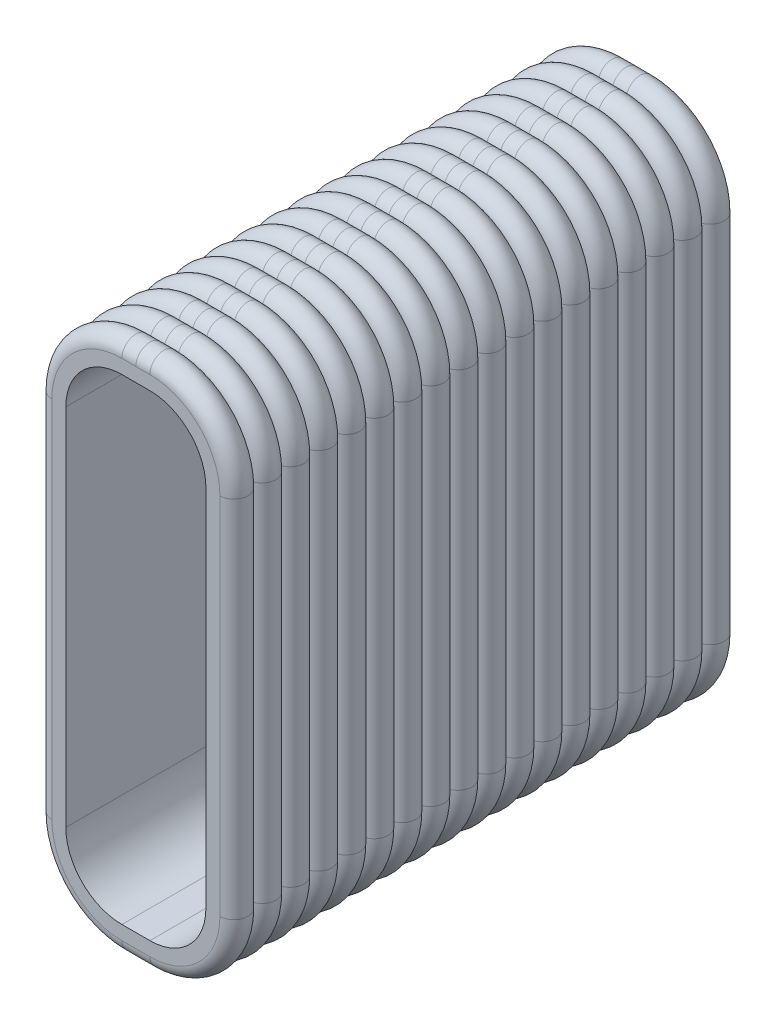
SolidWorks part; units mm, degrees
material "Copper-Cobalt-Beryllium alloy, UNS C17500"
ref_plane "Front Plane" through (0, 0, 0) normal (0, 0, 1) x (1, 0, 0)
ref_plane "Top Plane" through (0, 0, 0) normal (0, 1, 0) x (1, 0, 0)
ref_plane "Right Plane" through (0, 0, 0) normal (1, 0, 0) x (0, 0, -1)
sketch "Sketch1" plane through (0, 0, 0) normal (0, 0, 1) x (1, 0, 0)
  line L0 (-1.75, 3.25) -> (-1.75, -3.25)
  line L1 (-0.25, 4.25) -> (0.25, 4.25)
  line L2 (-1.25, 3.25) -> (-1.25, -3.25)
  line L3 (-0.25, -4.25) -> (0.25, -4.25)
  line L4 (1.25, 3.25) -> (1.25, -3.25)
  line L5 (-1.25, 4.25) -> (1.25, -4.25) construction
  line L6 (-1.25, -4.25) -> (1.25, 4.25) construction
  line L7 (-0.25, -4.75) -> (0.25, -4.75)
  line L8 (1.75, 3.25) -> (1.75, -3.25)
  line L9 (-0.25, 4.75) -> (0.25, 4.75)
  arc A2 (0.25, -4.25) -> (1.25, -3.25) centre (0.25, -3.25) ccw
  arc A3 (-1.25, -3.25) -> (-0.25, -4.25) centre (-0.25, -3.25) ccw
  arc A4 (0.25, 4.25) -> (1.25, 3.25) centre (0.25, 3.25) cw
  arc A5 (-0.25, 4.25) -> (-1.25, 3.25) centre (-0.25, 3.25) ccw
  arc A6 (-1.75, -3.25) -> (-0.25, -4.75) centre (-0.25, -3.25) ccw
  arc A7 (0.25, -4.75) -> (1.75, -3.25) centre (0.25, -3.25) ccw
  arc A8 (0.25, 4.75) -> (1.75, 3.25) centre (0.25, 3.25) cw
  arc A9 (-0.25, 4.75) -> (-1.75, 3.25) centre (-0.25, 3.25) ccw
  point P0 (0, 0)
  dimension "D2" = 1
  dimension "D1" = 2.5
  dimension "D3" = 6.5
  dimension "D4" = 0.5
extrude "Boss-Extrude1" add sketch "Sketch1" against normal blind 9
sketch "Sketch2" plane through (0, 0, 0) normal (1, 0, 0) x (0, 0, -1)
  line L0 (9, 4.75) -> (0, 4.75) construction
  line L1 (0, 4.75) -> (0.5, 4.75) construction
  line L3 (0.5, 4.75) -> (0.5, 4.5)
  line L4 (0, 4.75) -> (0, 4.5)
  line L6 (0, 4.75) -> (0, 5.25)
  line L7 (0, 5.25) -> (0.5, 5.25)
  line L8 (0.5, 5.25) -> (0.5, 4.75)
  arc A0 (0.5, 4.5) -> (0, 4.5) centre (0.25, 4.5) ccw
  dimension "D1" = 0.5
  dimension "D2" = 0.5
sketch "Sketch3" plane through (0, 0, 0) normal (0, 0, 1) x (1, 0, 0)
  line L4 (0.25, 4.75) -> (-0.25, 4.75) construction
  line L5 (-1.75, 3.25) -> (-1.75, -3.25) construction
  line L6 (-0.25, -4.75) -> (0.25, -4.75) construction
  line L7 (1.75, -3.25) -> (1.75, 3.25) construction
  line L8 (0.25, 4.75) -> (-0.25, 4.75)
  line L9 (-1.75, 3.25) -> (-1.75, -3.25)
  line L10 (-0.25, -4.75) -> (0.25, -4.75)
  line L11 (1.75, -3.25) -> (1.75, 3.25)
  arc A4 (-0.25, 4.75) -> (-1.75, 3.25) centre (-0.25, 3.25) ccw construction
  arc A5 (-1.75, -3.25) -> (-0.25, -4.75) centre (-0.25, -3.25) ccw construction
  arc A6 (0.25, -4.75) -> (1.75, -3.25) centre (0.25, -3.25) ccw construction
  arc A7 (1.75, 3.25) -> (0.25, 4.75) centre (0.25, 3.25) ccw construction
  arc A8 (-0.25, 4.75) -> (-1.75, 3.25) centre (-0.25, 3.25) ccw
  arc A9 (-1.75, -3.25) -> (-0.25, -4.75) centre (-0.25, -3.25) ccw
  arc A10 (0.25, -4.75) -> (1.75, -3.25) centre (0.25, -3.25) ccw
  arc A11 (1.75, 3.25) -> (0.25, 4.75) centre (0.25, 3.25) ccw
sweep "Cut-Sweep3" cut profiles "Sketch2" path "Sketch3"
pattern_linear "LPattern1" count 18 spacing 0.5 along (0, 0, -1) of "Cut-Sweep3"
